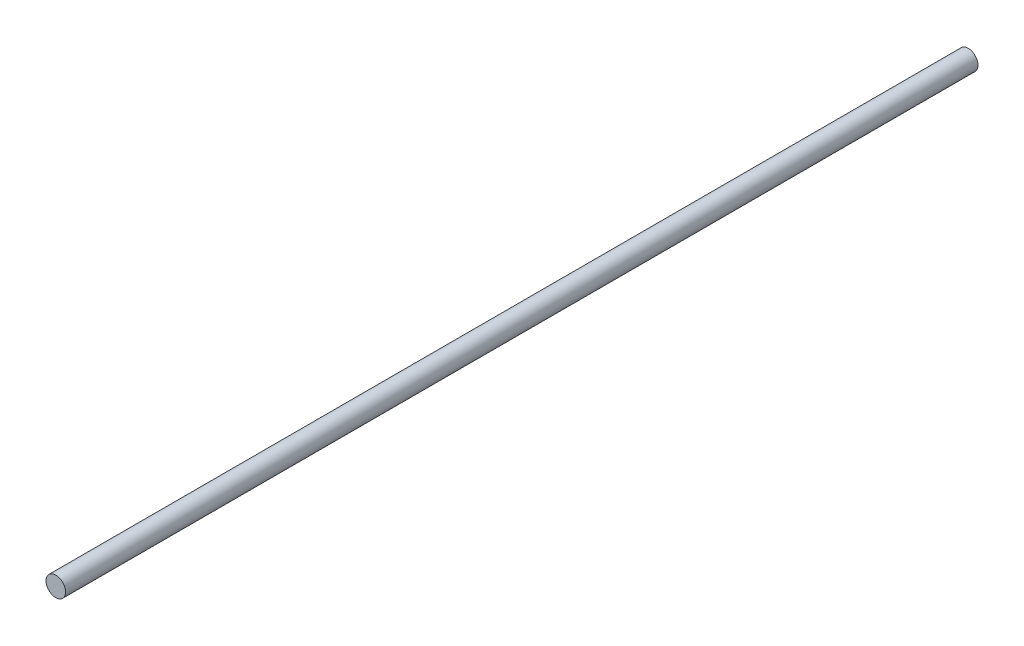
SolidWorks part; units mm, degrees
ref_plane "Front Plane" through (0, 0, 0) normal (0, 0, 1) x (1, 0, 0)
ref_plane "Top Plane" through (0, 0, 0) normal (0, 1, 0) x (1, 0, 0)
ref_plane "Right Plane" through (0, 0, 0) normal (1, 0, 0) x (0, 0, -1)
sketch "Sketch1" plane through (0, 0, 0) normal (0, 0, 1) x (1, 0, 0)
  circle A0 centre (0, 0) radius 7.5
  dimension "D1" = 15
extrude "Boss-Extrude1" add sketch "Sketch1" along normal blind 700
